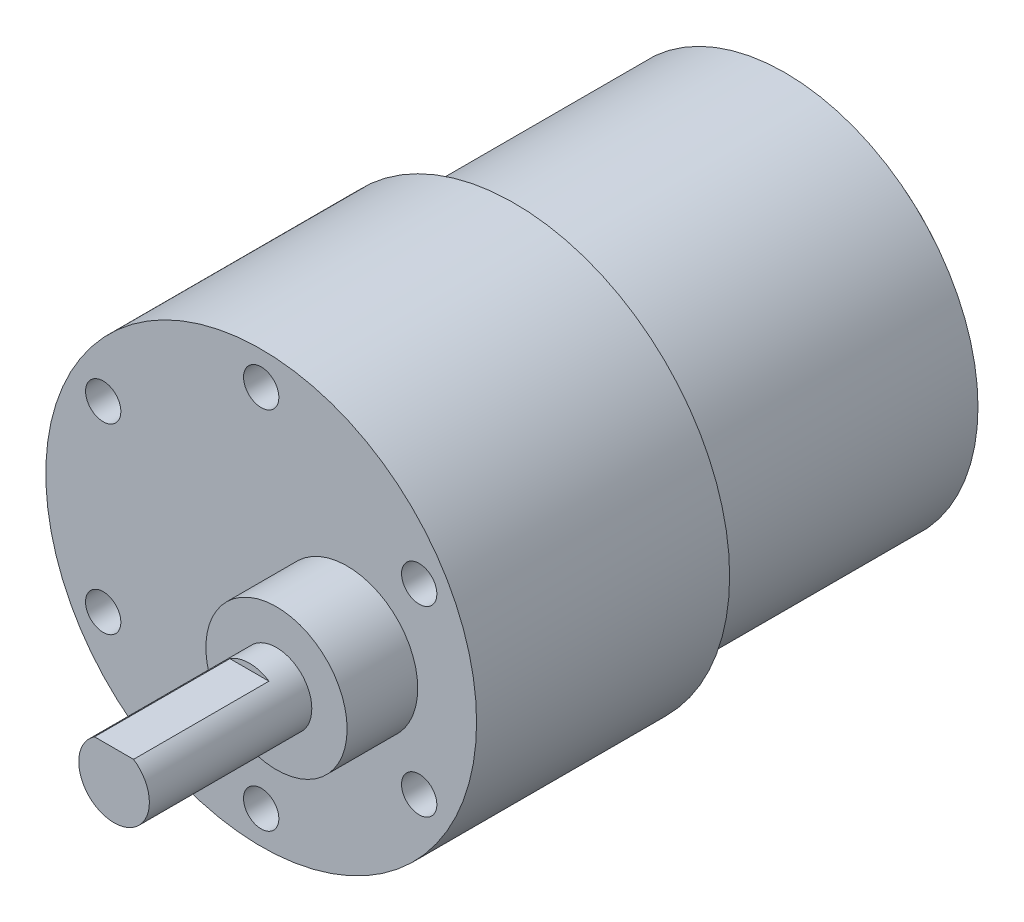
SolidWorks part; units mm, degrees
ref_plane "前视基准面" through (0, 0, 0) normal (0, 0, 1) x (1, 0, 0)
ref_plane "上视基准面" through (0, 0, 0) normal (0, 1, 0) x (1, 0, 0)
ref_plane "右视基准面" through (0, 0, 0) normal (1, 0, 0) x (0, 0, -1)
other "Configuration Table"
sketch "草图1" plane through (0, 0, 0) normal (0, 0, 1) x (1, 0, 0)
  circle A0 centre (0, 0) radius 18.3
  dimension "D1" = 36.6
extrude "凸台-拉伸1" add sketch "草图1" along normal blind 21.5
sketch "草图2" plane through (0, 0, 21.5) normal (0, 0, 1) x (1, 0, 0)
  circle A0 centre (0, 0) radius 15.5
  circle A1 centre (0, 15.5) radius 1.5
  circle A2 centre (13.4234, 7.75) radius 1.5
  circle A3 centre (13.4234, -7.75) radius 1.5
  circle A4 centre (0, -15.5) radius 1.5
  circle A5 centre (-13.4234, -7.75) radius 1.5
  circle A6 centre (-13.4234, 7.75) radius 1.5
  point P17 (0, 0)
  dimension "D1" = 31
  dimension "D2" = 3
  dimension "D3" = 6
extrude "切除-拉伸1" cut sketch "草图2" against normal blind 5 contours A6 | A1 | A2 | A3 | A4 | A5
sketch "草图3" plane through (0, 0, 21.5) normal (0, 0, 1) x (1, 0, 0)
  line L0 (-18.3, 0) -> (18.3, 0) construction
  circle A0 centre (0, 0) radius 18.3 construction
  circle A1 centre (7.3, 0) radius 6
  point P7 (0, 15.5)
  dimension "D1" = 12
  dimension "D2" = 7.3
extrude "凸台-拉伸2" add sketch "草图3" along normal blind 6
sketch "草图4" plane through (0, 0, 27.5) normal (0, 0, 1) x (1, 0, 0)
  circle A0 centre (7.3, 0) radius 3
  dimension "D1" = 6
extrude "凸台-拉伸3" add sketch "草图4" along normal blind 13.8
sketch "草图5" plane through (0, 0, 41.3) normal (0, 0, 1) x (1, 0, 0)
  line L0 (4.3, 0) -> (10.3, 0) construction
  line L1 (5.6417, 2.5) -> (8.9583, 2.5)
  circle A0 centre (7.3, 0) radius 3 construction
  circle A1 centre (7.3, 0) radius 3 construction
  arc A2 (5.6417, 2.5) -> (8.9583, 2.5) centre (7.3, 0) cw
  dimension "D1" = 2.5
extrude "切除-拉伸2" cut sketch "草图5" against normal blind 11.5
sketch "草图6" plane through (0, 0, 0) normal (0, 0, -1) x (-1, 0, 0)
  circle A0 centre (0, 0) radius 16.4
  dimension "D1" = 32.8
extrude "凸台-拉伸4" add sketch "草图6" along normal blind 23
sketch "草图7" plane through (0, 0, -23) normal (0, 0, -1) x (-1, 0, 0)
  circle A0 centre (0, 0) radius 15
  dimension "D1" = 30
extrude "凸台-拉伸5" add sketch "草图7" along normal blind 1
sketch "草图8" plane through (0, 0, -24) normal (0, 0, -1) x (-1, 0, 0)
  circle A0 centre (0, 0) radius 3
  dimension "D1" = 6
extrude "凸台-拉伸6" add sketch "草图8" along normal blind 4
sketch "草图9" plane through (0, 0, -24) normal (0, 0, -1) x (-1, 0, 0)
  line L5 (-6.0808, -14.0413) -> (6.0808, -14.0413)
  line L6 (-6.0808, -14.0413) -> (-6.0808, -9.5408)
  line L7 (-6.0808, -9.5408) -> (6.0808, -9.5408)
  line L8 (6.0808, -14.0413) -> (6.0808, -9.5408)
  line L9 (-6.0808, -14.0413) -> (6.0808, -9.5408) construction
  line L10 (-6.0808, -9.5408) -> (6.0808, -14.0413) construction
  point P0 (0, -11.791)
extrude "凸台-拉伸7" add sketch "草图9" along normal blind 7.9
sketch "草图10" plane through (0, 0, -24) normal (0, 0, -1) x (-1, 0, 0)
  line L1 (-5.8897, -1.3556) -> (-4.6897, -1.3556)
  line L2 (-5.8897, -1.3556) -> (-5.8897, 1.3556)
  line L3 (-5.8897, 1.3556) -> (-4.6897, 1.3556)
  line L4 (-4.6897, -1.3556) -> (-4.6897, 1.3556)
  line L5 (-5.8897, -1.3556) -> (-4.6897, 1.3556) construction
  line L6 (-5.8897, 1.3556) -> (-4.6897, -1.3556) construction
  line L7 (5.2352, -1.3556) -> (6.4352, -1.3556)
  line L8 (5.2352, -1.3556) -> (5.2352, 1.3556)
  line L9 (5.2352, 1.3556) -> (6.4352, 1.3556)
  line L10 (6.4352, -1.3556) -> (6.4352, 1.3556)
  line L11 (5.2352, -1.3556) -> (6.4352, 1.3556) construction
  line L12 (5.2352, 1.3556) -> (6.4352, -1.3556) construction
  point P0 (-5.2897, 0)
  point P5 (5.8352, 0)
  dimension "D1" = 1.2
  dimension "D2" = 1.2
extrude "凸台-拉伸8" add sketch "草图10" along normal blind 4
sketch "草图11" plane through (0, 0, -31.9) normal (0, 0, -1) x (-1, 0, 0)
  line L0 (-6.0808, -14.0413) -> (6.0808, -14.0413) construction
  line L1 (-5.0899, -17.2261) -> (5.0899, -17.2261)
  line L2 (-5.0899, -17.2261) -> (-5.0899, -10.8565)
  line L3 (-5.0899, -10.8565) -> (5.0899, -10.8565)
  line L4 (5.0899, -17.2261) -> (5.0899, -10.8565)
  line L5 (-5.0899, -17.2261) -> (5.0899, -10.8565) construction
  line L6 (-5.0899, -10.8565) -> (5.0899, -17.2261) construction
  point P0 (0, -14.0413)
extrude "切除-拉伸3" cut sketch "草图11" against normal blind 6
